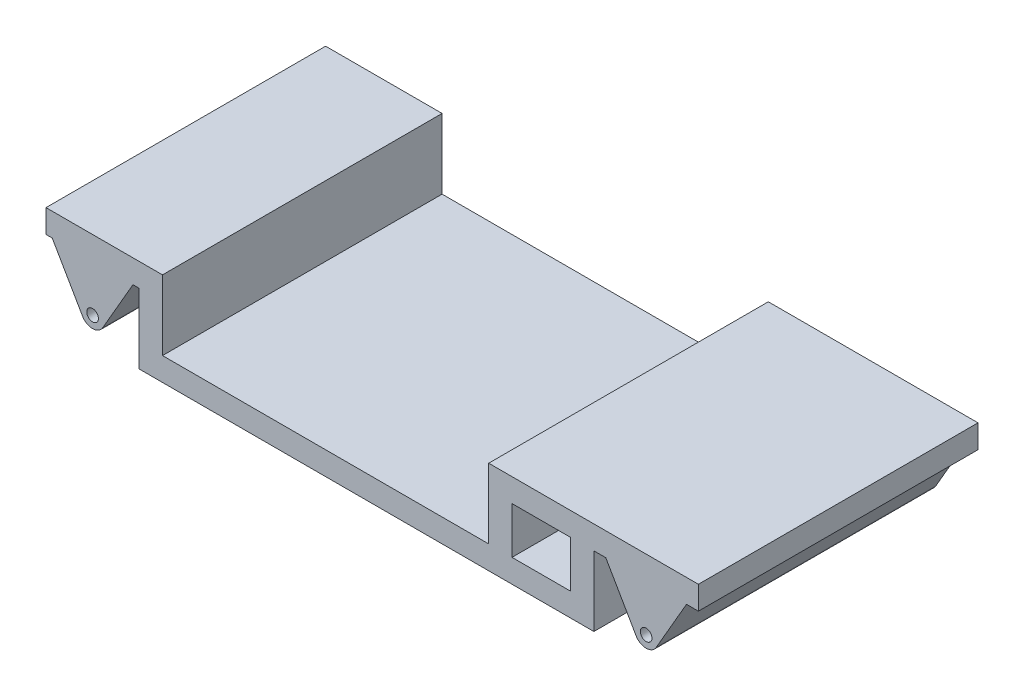
SolidWorks part; units mm, degrees
material "AISI 1020 Steel, Cold Rolled"
ref_plane "Front Plane" through (0, 0, 0) normal (0, 0, 1) x (1, 0, 0)
ref_plane "Top Plane" through (0, 0, 0) normal (0, 1, 0) x (1, 0, 0)
ref_plane "Right Plane" through (0, 0, 0) normal (1, 0, 0) x (0, 0, -1)
sketch "Sketch4" plane through (0, 0, 0) normal (0, 0, 1) x (1, 0, 0)
  line L0 (1251.4244, 524.9024) -> (1000, 524.9024)
  line L1 (-600, 224.9024) -> (1200, 224.9024)
  line L2 (-1000, 524.9024) -> (-1000, 624.9024)
  line L3 (-1000, 624.9024) -> (-500, 624.9024)
  line L4 (1800, 524.9024) -> (1800, 624.9024)
  line L5 (1200, 224.9024) -> (1351.4244, 224.9024)
  line L6 (900, 624.9024) -> (1800, 624.9024)
  line L7 (-600, 524.9024) -> (-626.7949, 524.9024)
  line L8 (-600, 224.9024) -> (-600, 524.9024)
  line L9 (1800, 524.9024) -> (1748.9173, 524.9024)
  line L10 (1000, 324.9024) -> (1000, 524.9024)
  line L11 (1000, 324.9024) -> (1251.4244, 324.9024)
  line L13 (1351.4244, 224.9024) -> (1351.4244, 524.9024)
  line L14 (-843.3013, 299.9024) -> (-973.2051, 524.9024)
  line L15 (1251.4244, 324.9024) -> (1251.4244, 524.9024)
  line L16 (-500, 624.9024) -> (-500, 324.9024)
  line L17 (-500, 324.9024) -> (900, 324.9024)
  line L18 (900, 624.9024) -> (900, 324.9024)
  line L19 (-756.6987, 299.9024) -> (-626.7949, 524.9024)
  line L20 (1532.4109, 299.9024) -> (1402.5071, 524.9024)
  line L21 (1619.0135, 299.9024) -> (1748.9173, 524.9024)
  line L22 (1402.5071, 524.9024) -> (1351.4244, 524.9024)
  line L23 (-973.2051, 524.9024) -> (-1000, 524.9024)
  line L24 (-800, 400) -> (-800, 112.8797) construction
  line L25 (1575.7122, 400) -> (1575.7122, 85.9395) construction
  circle A0 centre (-800, 324.9024) radius 25
  arc A1 (-843.3013, 299.9024) -> (-756.6987, 299.9024) centre (-800, 324.9024) ccw
  arc A2 (1532.4109, 299.9024) -> (1619.0135, 299.9024) centre (1575.7122, 324.9024) ccw
  circle A3 centre (1575.7122, 324.9024) radius 25
  dimension "D17" = 50
  dimension "D19" = 200
  dimension "D20" = 100
  dimension "D24" = 200
  dimension "D25" = 50
  dimension "D26" = 100
  dimension "D3" = 500
  dimension "D4" = 300
  dimension "D5" = 100
  dimension "D6" = 100
  dimension "D7" = 100
  dimension "D8" = 100
  dimension "D9" = 100
  dimension "D10" = 100
  dimension "D11" = 900
  dimension "D12" = 251.4244
  dimension "D13" = 1400
  dimension "D14" = 100
  dimension "D21" = 60
  dimension "D27" = 60
extrude "Boss-Extrude3" add sketch "Sketch4" against normal blind 1200
